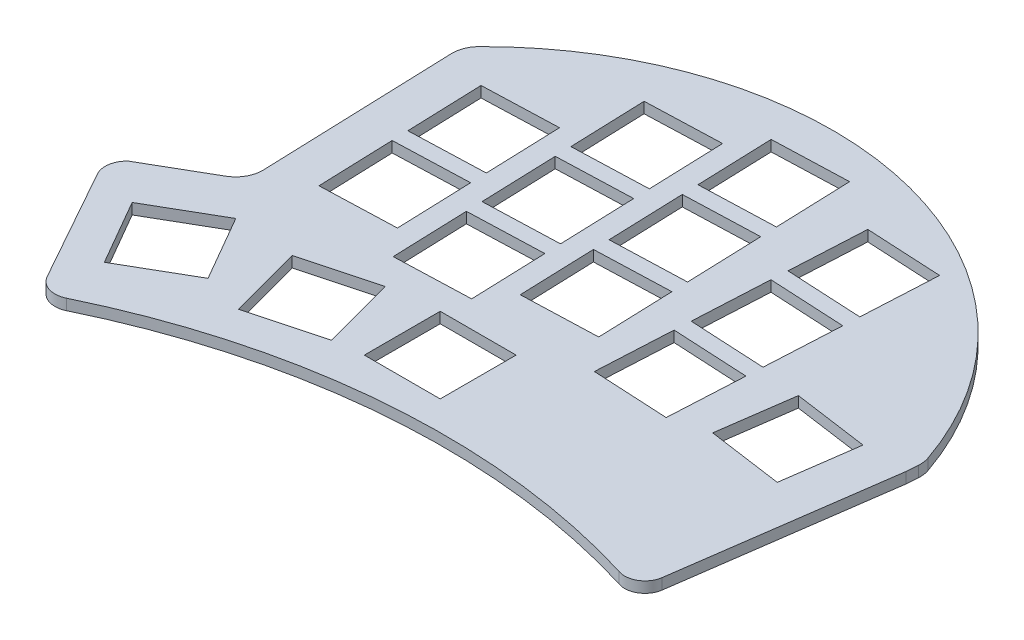
SolidWorks part; units mm, degrees
ref_plane "Front Plane" through (0, 0, 0) normal (0, 0, 1) x (1, 0, 0)
ref_plane "Top Plane" through (0, 0, 0) normal (0, 1, 0) x (1, 0, 0)
ref_plane "Right Plane" through (0, 0, 0) normal (1, 0, 0) x (0, 0, -1)
sketch "Sketch2" plane through (0, 0, 0) normal (0, 1, 0) x (1, 0, 0)
  line L0 (-1095.7696, -1082.6393) -> (-1107.542, -1061.5848)
  line L1 (-1106.7573, -1056.6874) -> (-1095.3591, -1050.1067)
  line L2 (-1092.8591, -1045.7766) -> (-1094.1155, -1009.711)
  line L3 (-985.2486, -1032.3695) -> (-985.4049, -1034.5557)
  line L4 (-985.4049, -1034.5557) -> (-990.9456, -1073.98)
  line L5 (-1086.2946, -1012.0583) -> (-1072.3031, -1011.5697)
  line L6 (-1086.2946, -1012.0583) -> (-1085.8061, -1026.0458)
  line L7 (-1072.3031, -1011.5697) -> (-1071.8147, -1025.5572)
  line L8 (-1085.8061, -1026.0458) -> (-1071.8147, -1025.5572)
  line L9 (-1068.7209, -999.5373) -> (-1068.2323, -1013.5288)
  line L10 (-1068.7209, -999.5373) -> (-1054.7332, -999.0489)
  line L11 (-1068.2323, -1013.5288) -> (-1054.2446, -1013.0403)
  line L12 (-1054.7332, -999.0489) -> (-1054.2446, -1013.0403)
  line L13 (-1050.9063, -993.9122) -> (-1036.9149, -993.4236)
  line L14 (-1050.9063, -993.9122) -> (-1050.4177, -1007.9044)
  line L15 (-1036.9149, -993.4236) -> (-1036.4262, -1007.4158)
  line L16 (-1050.4177, -1007.9044) -> (-1036.4262, -1007.4158)
  line L17 (-1027.6134, -999.3726) -> (-1013.6326, -1000.1053)
  line L18 (-1027.6134, -999.3726) -> (-1028.3464, -1013.3584)
  line L19 (-1013.6326, -1000.1053) -> (-1014.3656, -1014.0911)
  line L20 (-1028.3464, -1013.3584) -> (-1014.3656, -1014.0911)
  line L21 (-1028.5032, -1016.3493) -> (-1014.5223, -1017.082)
  line L22 (-1028.5032, -1016.3493) -> (-1029.2359, -1030.3301)
  line L23 (-1014.5223, -1017.082) -> (-1015.255, -1031.0628)
  line L24 (-1029.2359, -1030.3301) -> (-1015.255, -1031.0628)
  line L25 (-1029.3929, -1033.326) -> (-1015.412, -1034.0587)
  line L26 (-1029.3929, -1033.326) -> (-1030.1256, -1047.3078)
  line L27 (-1015.412, -1034.0587) -> (-1016.1448, -1048.0405)
  line L28 (-1030.1256, -1047.3078) -> (-1016.1448, -1048.0405)
  line L29 (-1007.4577, -1032.3324) -> (-993.5939, -1034.2808)
  line L30 (-1007.4577, -1032.3324) -> (-1009.4062, -1046.1967)
  line L31 (-993.5939, -1034.2808) -> (-995.5424, -1048.1452)
  line L32 (-1009.4062, -1046.1967) -> (-995.5424, -1048.1452)
  line L33 (-1050.313, -1010.9018) -> (-1036.3216, -1010.4132)
  line L34 (-1050.313, -1010.9018) -> (-1049.8243, -1024.8966)
  line L35 (-1036.3216, -1010.4132) -> (-1035.8329, -1024.408)
  line L36 (-1049.8243, -1024.8966) -> (-1035.8329, -1024.408)
  line L37 (-1068.1276, -1016.527) -> (-1054.1361, -1016.0384)
  line L38 (-1068.1276, -1016.527) -> (-1067.6391, -1030.5166)
  line L39 (-1054.1361, -1016.0384) -> (-1053.6476, -1030.028)
  line L40 (-1067.6391, -1030.5166) -> (-1053.6476, -1030.028)
  line L41 (-1067.5343, -1033.5166) -> (-1053.5428, -1033.028)
  line L42 (-1067.5343, -1033.5166) -> (-1067.0456, -1047.5108)
  line L43 (-1053.5428, -1033.028) -> (-1053.0541, -1047.0222)
  line L44 (-1067.0456, -1047.5108) -> (-1053.0541, -1047.0222)
  line L45 (-1085.7013, -1029.0479) -> (-1071.7098, -1028.5593)
  line L46 (-1085.7013, -1029.0479) -> (-1085.2127, -1043.039)
  line L47 (-1071.7098, -1028.5593) -> (-1071.2213, -1042.5504)
  line L48 (-1085.2127, -1043.039) -> (-1071.2213, -1042.5504)
  line L49 (-1049.7198, -1027.8915) -> (-1035.7283, -1027.4029)
  line L50 (-1049.7198, -1027.8915) -> (-1049.2313, -1041.8794)
  line L51 (-1035.7283, -1027.4029) -> (-1035.2398, -1041.3908)
  line L52 (-1049.2313, -1041.8794) -> (-1035.2398, -1041.3908)
  line L53 (-1053.9732, -1051.9054) -> (-1039.9732, -1051.9054)
  line L54 (-1053.9732, -1051.9054) -> (-1053.9732, -1065.9089)
  line L55 (-1039.9732, -1051.9054) -> (-1039.9732, -1065.9089)
  line L56 (-1053.9732, -1065.9089) -> (-1039.9732, -1065.9089)
  line L57 (-1076.5464, -1056.6557) -> (-1063.0234, -1053.0322)
  line L58 (-1076.5464, -1056.6557) -> (-1072.9223, -1070.181)
  line L59 (-1063.0234, -1053.0322) -> (-1059.3993, -1066.5575)
  line L60 (-1072.9223, -1070.181) -> (-1059.3993, -1066.5575)
  line L61 (-1099.7863, -1062.9348) -> (-1092.7863, -1075.0592)
  line L62 (-1099.7863, -1062.9348) -> (-1087.6611, -1055.9343)
  line L63 (-1092.7863, -1075.0592) -> (-1080.6611, -1068.0586)
  line L64 (-1087.6611, -1055.9343) -> (-1080.6611, -1068.0586)
  arc A0 (-1107.542, -1061.5848) -> (-1106.7573, -1056.6874) centre (-1104.0507, -1059.6326) cw
  arc A1 (-1095.3591, -1050.1067) -> (-1092.8591, -1045.7766) centre (-1097.8591, -1045.7766) ccw
  arc A3 (-1094.1155, -1009.711) -> (-1092.6791, -1006.0262) centre (-1089.1175, -1009.5369) cw
  arc A4 (-1092.6791, -1006.0262) -> (-985.5077, -1030.3867) centre (-1046.6401, -1051.4074) cw
  arc A5 (-985.5077, -1030.3867) -> (-985.2486, -1032.3695) centre (-990.238, -1032.0132) cw
  arc A6 (-990.9456, -1073.98) -> (-995.9919, -1076.939) centre (-994.6409, -1073.4606) cw
  arc A7 (-1095.7696, -1082.6393) -> (-1090.5339, -1084.2868) centre (-1092.2783, -1080.6872) ccw
  arc A8 (-1090.5339, -1084.2868) -> (-995.9919, -1076.939) centre (-1033.8933, -1201.1691) cw
extrude "Boss-Extrude1" add sketch "Sketch2" along normal blind 2 contours L64 L62 L61 L63 | L46 L48 L47 L45 | L6 L8 L7 L5 | L12 L10 L9 L11 | L38 L40 L39 L37 | L58 L60 L59 L57 | L54 L56 L55 L53 | L42 L44 L43 L41 | L50 L52 L51 L49 | L34 L36 L35 L33 | L14 L16 L15 L13 | L18 L20 L19 L17 | L22 L24 L23 L21 | L26 L28 L27 L25 | L30 L32 L31 L29 | L2 A3 A4 A5 L3 L4 A6 A8 A7 L0 A0 L1 A1
